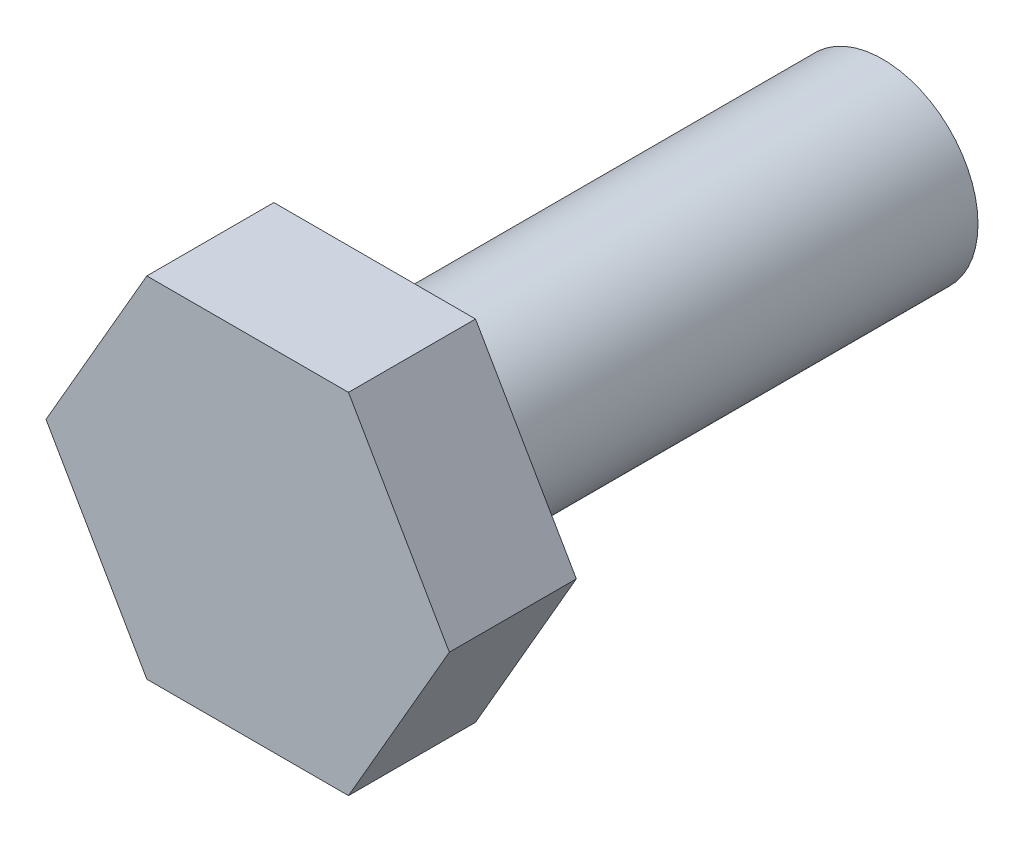
SolidWorks part; units mm, degrees
material "AISI 304"
ref_plane "Front Plane" through (0, 0, 0) normal (0, 0, 1) x (1, 0, 0)
ref_plane "Top Plane" through (0, 0, 0) normal (0, 1, 0) x (1, 0, 0)
ref_plane "Right Plane" through (0, 0, 0) normal (1, 0, 0) x (0, 0, -1)
sketch "Sketch1" plane through (0, 0, 0) normal (0, 0, 1) x (1, 0, 0)
  circle A0 centre (0, 0) radius 1.5
  dimension "D1" = 3
extrude "Extrude1" add sketch "Sketch1" against normal blind 8
cosmetic thread "Cosmetic Thread1" parameters "D1"=8, "D2"=6.5278
sketch "Sketch2" plane through (0, 0, 0) normal (0, 0, 1) x (1, 0, 0)
  line L1 (-1.5877, 2.75) -> (-3.1754, 0)
  line L2 (-3.1754, 0) -> (-1.5877, -2.75)
  line L3 (-1.5877, -2.75) -> (1.5877, -2.75)
  line L4 (1.5877, -2.75) -> (3.1754, 0)
  line L5 (3.1754, 0) -> (1.5877, 2.75)
  line L6 (1.5877, 2.75) -> (-1.5877, 2.75)
  circle A0 centre (0, 0) radius 2.75 construction
  dimension "D1" = 5.5
extrude "Extrude2" add sketch "Sketch2" along normal blind 2
